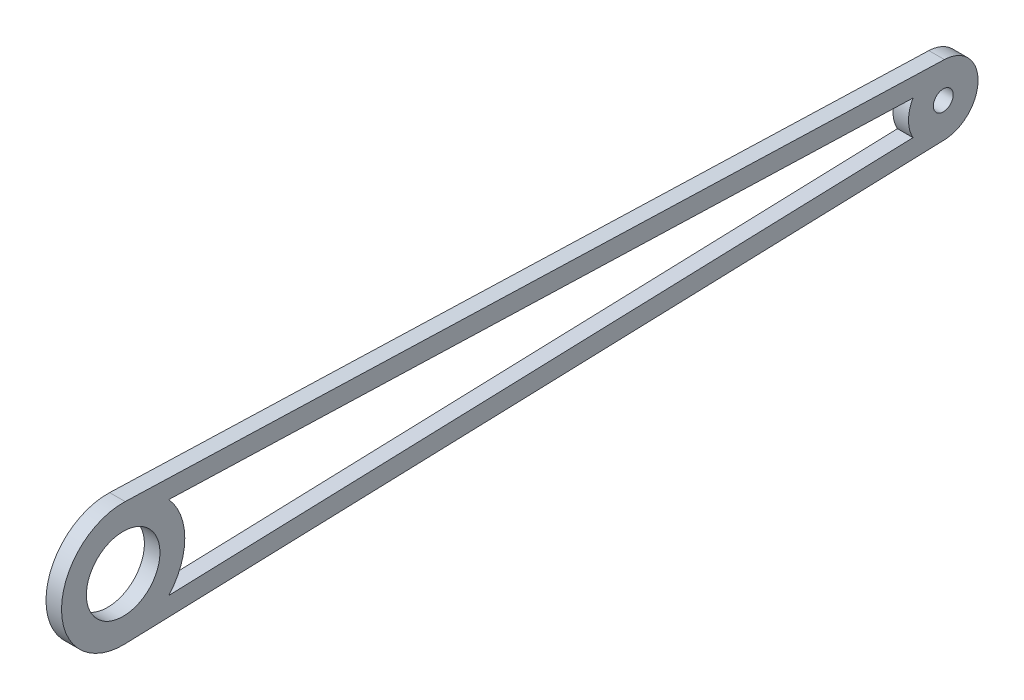
SolidWorks part; units mm, degrees
material "Delrin"
ref_plane "Front Plane" through (0, 0, 0) normal (0, 0, 1) x (1, 0, 0)
ref_plane "Top Plane" through (0, 0, 0) normal (0, 1, 0) x (1, 0, 0)
ref_plane "Right Plane" through (0, 0, 0) normal (1, 0, 0) x (0, 0, -1)
sketch "Sketch1" plane through (0, 0, 0) normal (1, 0, 0) x (0, 0, -1)
  line L0 (0.2062, 6.2958) -> (83.9364, 3.5541)
  line L1 (0, -6.3026) -> (83.9364, -3.5541)
  line L2 (-1000, 0) -> (49000, 0) construction
  line L3 (4.6548, 4.2441) -> (80.7262, 1.7532)
  line L4 (4.6548, -4.2441) -> (80.7262, -1.7532)
  line L5 (0.1438, 4.3918) -> (83.874, 1.6501) construction
  line L6 (-0.0623, -4.3986) -> (83.874, -1.6501) construction
  line L7 (83.82, -1000) -> (83.82, 49000) construction
  circle A0 centre (0, 0) radius 3.7592
  circle A1 centre (0, 0) radius 6.2992
  circle A2 centre (83.82, 0) radius 1.016
  circle A3 centre (83.82, 0) radius 3.556
  circle A4 centre (83.82, 15.875) radius 1.016
  circle A5 centre (83.82, 15.875) radius 3.556
  dimension "D1" = 7.5184
  dimension "D2" = 2.54
  dimension "D3" = 2.032
  dimension "D8" = 2.032
  dimension "D5" = 83.82
  dimension "D10" = 15.875
  dimension "D4" = 2.54
  dimension "D6" = 1.905
  dimension "D7" = 1.905
  dimension "D9" = 2.54
extrude "Boss-Extrude1" add sketch "Sketch1" along normal blind 1.5875 contours L2 A1 A0 | A1 L2 A0 | A1 L2 A3 L0 | L2 A1 L1 A3 | L2 A3 A2 | A3 L2 A2
sketch3d "3DSketch1"
  line L0 (0, 6.2958, -0.2062) -> (0, 3.5541, -83.9364) construction
  line L1 (0, 3.5912, -82.804) -> (1.5875, 3.5912, -82.804)
  line L2 (0, 3.5912, -82.804) -> (0, -3.5912, -82.804)
  line L3 (0, -3.5912, -82.804) -> (1.5875, -3.5912, -82.804)
  line L4 (1.5875, 3.5912, -82.804) -> (1.5875, -3.5912, -82.804)
  line L5 (1.5875, -6.2958, -0.2062) -> (1.5875, -3.5541, -83.9364) construction
